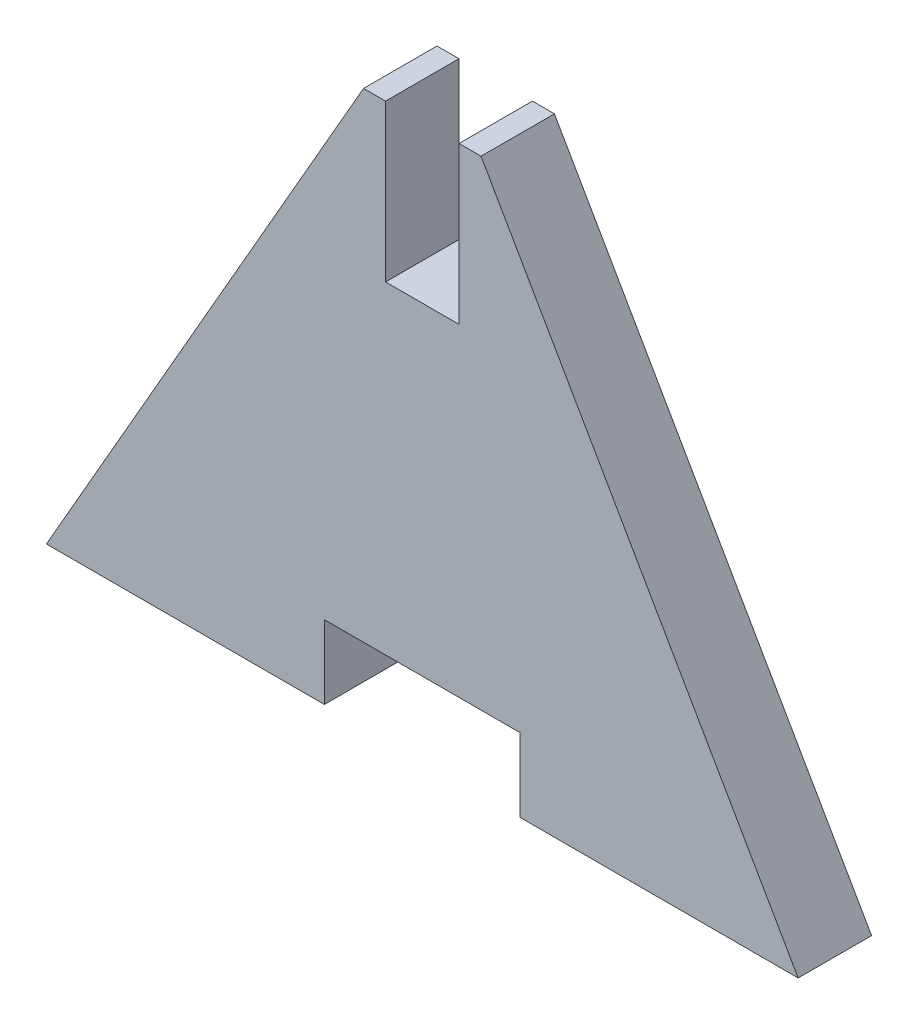
SolidWorks part; units mm, degrees
material "Balsa"
ref_plane "Front Plane" through (0, 0, 0) normal (0, 0, 1) x (1, 0, 0)
ref_plane "Top Plane" through (0, 0, 0) normal (0, 1, 0) x (1, 0, 0)
ref_plane "Right Plane" through (0, 0, 0) normal (1, 0, 0) x (0, 0, -1)
sketch "Sketch1" plane through (0, 0, 0) normal (0, 0, 1) x (1, 0, 0)
  line L0 (0, 0) -> (76.5962, 0) construction
  line L1 (0, 0) -> (0, -47.5265) construction
  line L2 (0, 42.5274) -> (24.384, 0)
  line L3 (24.384, 0) -> (-24.384, 0)
  line L4 (0, 42.5274) -> (-24.384, 0)
  point P11 (0, 0)
  dimension "D1" = 24.384
  dimension "D2" = 49.022
extrude "Boss-Extrude1" add sketch "Sketch1" along normal blind 4.7625
sketch "Sketch2" plane through (0, 0, 4.7625) normal (0, 0, 1) x (1, 0, 0)
  line L0 (0, 0) -> (-6.35, 0)
  line L1 (-24.384, 0) -> (24.384, 0) construction
  line L2 (-6.35, 0) -> (-6.35, 4.7625)
  line L3 (-6.35, 4.7625) -> (6.35, 4.7625)
  line L4 (6.35, 4.7625) -> (6.35, 0)
  line L5 (6.35, 0) -> (0, 0)
  line L6 (0, 42.5274) -> (-3.81, 35.8825)
  line L7 (0, 42.5274) -> (-24.384, 0) construction
  line L8 (-3.81, 35.8825) -> (3.81, 35.8825)
  line L9 (24.384, 0) -> (0, 42.5274) construction
  line L10 (3.81, 35.8825) -> (0, 42.5274)
  dimension "D1" = 6.35
  dimension "D2" = 4.7625
  dimension "D3" = 7.62
extrude "Cut-Extrude1" cut sketch "Sketch2" against normal through all
sketch "Sketch4" plane through (0, 35.8825, 0) normal (0, 1, 0) x (1, 0, 0)
  line L0 (0, 0) -> (0, -4.7625) construction
  line L1 (-3.81, 0) -> (3.81, 0) construction
  line L2 (-3.81, -4.7625) -> (3.81, -4.7625) construction
  line L4 (-2.3812, 0) -> (2.3812, 0)
  line L5 (-2.3812, 0) -> (-2.3812, -4.7625)
  line L6 (-2.3812, -4.7625) -> (2.3812, -4.7625)
  line L7 (2.3812, 0) -> (2.3812, -4.7625)
  line L8 (-2.3812, 0) -> (2.3812, -4.7625) construction
  line L9 (-2.3812, -4.7625) -> (2.3812, 0) construction
  point P6 (0, -2.3812)
  dimension "D1" = 4.7625
extrude "Cut-Extrude2" cut sketch "Sketch4" against normal blind 10.16
